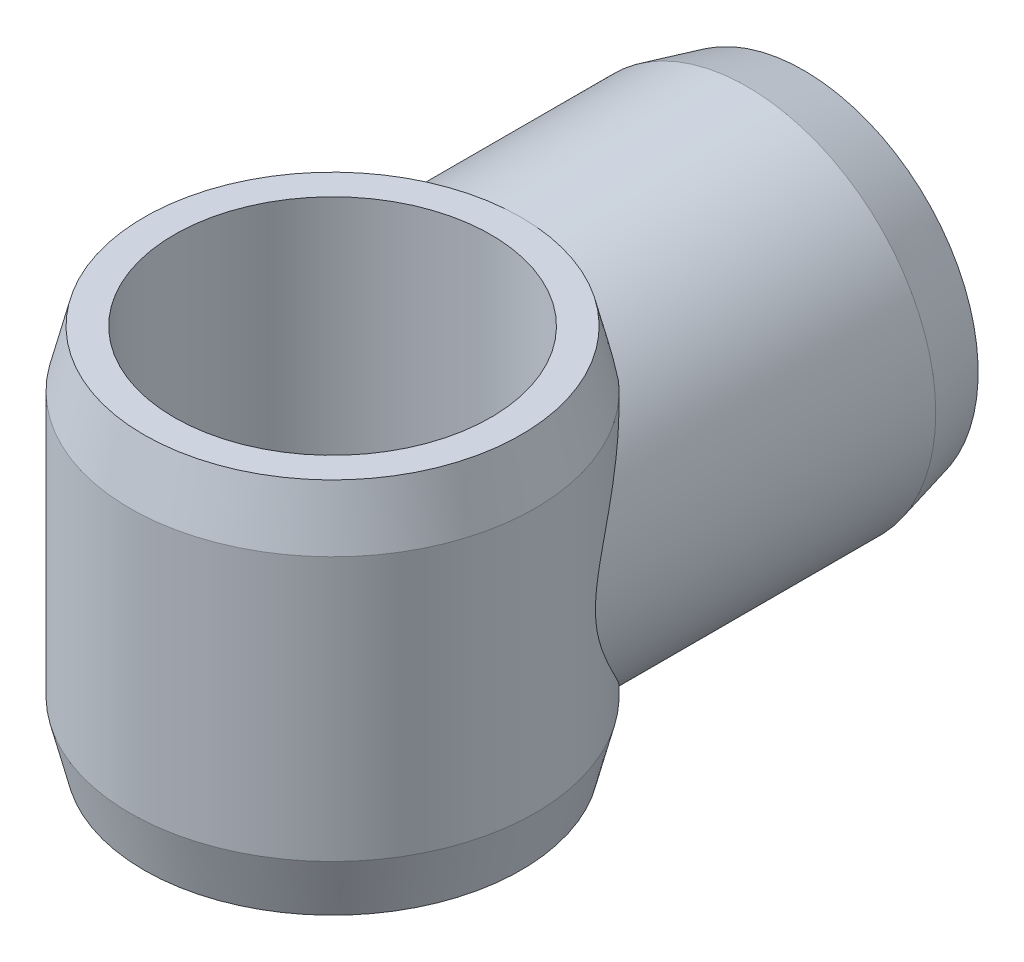
SolidWorks part; units mm, degrees
ref_plane "Front Plane" through (0, 0, 0) normal (0, 0, 1) x (1, 0, 0)
ref_plane "Top Plane" through (0, 0, 0) normal (0, 1, 0) x (1, 0, 0)
ref_plane "Right Plane" through (0, 0, 0) normal (1, 0, 0) x (0, 0, -1)
sketch "Sketch1" plane through (0, 0, 0) normal (0, 1, 0) x (1, 0, 0)
  circle A0 centre (0, 0) radius 10.668
  circle A1 centre (0, 0) radius 13.6525
  dimension "D1" = 27.305
  dimension "D2" = 21.336
extrude "Boss-Extrude1" add sketch "Sketch1" along normal blind 25.4
ref_plane "Plane1" through (0, 0, -31.75) normal (0, 0, 1) x (1, 0, 0)
sketch "Sketch10" plane through (0, 0, 0) normal (1, 0, 0) x (0, 0, -1)
  line L0 (-13.6525, 0) -> (13.6525, 0) construction
  line L1 (-13.6525, 0) -> (13.6525, 0) construction
  line L2 (-13.6525, 0) -> (-13.6525, 3.81)
  line L3 (-13.6525, 25.4) -> (-13.6525, 0) construction
  line L4 (-13.6525, 3.81) -> (-12.7, 0)
  line L5 (-12.7, 0) -> (-13.6525, 0)
  line L6 (0, 0) -> (0, 24.0354) construction
  dimension "D1" = 0.9525
  dimension "D2" = 3.81
revolve "Cut-Revolve4" cut sketch "Sketch10" angle 360 about L6
ref_plane "Plane3" through (0, 12.7, 0) normal (0, 1, 0) x (1, 0, 0)
mirror "Mirror1" about plane through (0, 12.7, 0) normal (0, 1, 0) of "Cut-Revolve4"
sketch "Sketch4" plane through (0, 0, -31.75) normal (0, 0, 1) x (1, 0, 0)
  line L0 (0, 0) -> (0, 76.2) construction
  circle A0 centre (0, 12.7) radius 12.7
  circle A1 centre (0, 12.7) radius 10.668
  dimension "D2" = 25.4
  dimension "D3" = 21.336
  dimension "D1" = 76.2
  dimension "D4" = 12.7
extrude "Boss-Extrude2" add sketch "Sketch4" along normal up to body
ref_plane "Plane2" through (0, 12.7, 0) normal (0, 1, 0) x (1, 0, 0)
sketch "Sketch11" plane through (0, 0, 0) normal (1, 0, 0) x (0, 0, -1)
  line L0 (31.75, 0) -> (31.75, 25.4) construction
  line L1 (31.75, 0) -> (31.75, 25.4) construction
  line L2 (31.75, 0) -> (27.94, 0)
  line L3 (12.7, 0) -> (31.75, 0) construction
  line L4 (27.94, 0) -> (31.75, 0.9525)
  line L5 (31.75, 0.9525) -> (31.75, 0)
  line L6 (31.75, 12.7) -> (23.414, 12.7) construction
  dimension "D1" = 3.81
  dimension "D2" = 0.9525
revolve "Cut-Revolve5" cut sketch "Sketch11" angle 360 about L6
ref_plane "Plane5" through (0, 0, -31.75) normal (0, 0, -1) x (-1, 0, 0)
sketch "Sketch12" plane through (0, 0, -31.75) normal (0, 0, -1) x (-1, 0, 0)
  circle A0 centre (0, 12.7) radius 10.668 construction
  circle A1 centre (0, 12.7) radius 10.668
extrude "Cut-Extrude1" cut sketch "Sketch12" against normal blind 19.05
sketch "Sketch13" plane through (0, 0, -12.7) normal (0, 0, -1) x (-1, 0, 0)
  circle A0 centre (0, 12.7) radius 10.668 construction
  circle A1 centre (0, 12.7) radius 10.668
  circle A2 centre (0, 12.7) radius 9.398
  dimension "D1" = 21.336
  dimension "D2" = 18.796
extrude "Boss-Extrude4" add sketch "Sketch13" against normal up to body contours A2 | A1
ref_plane "Plane6" through (0, 12.7, 0) normal (0, -1, 0) x (-1, 0, 0)
